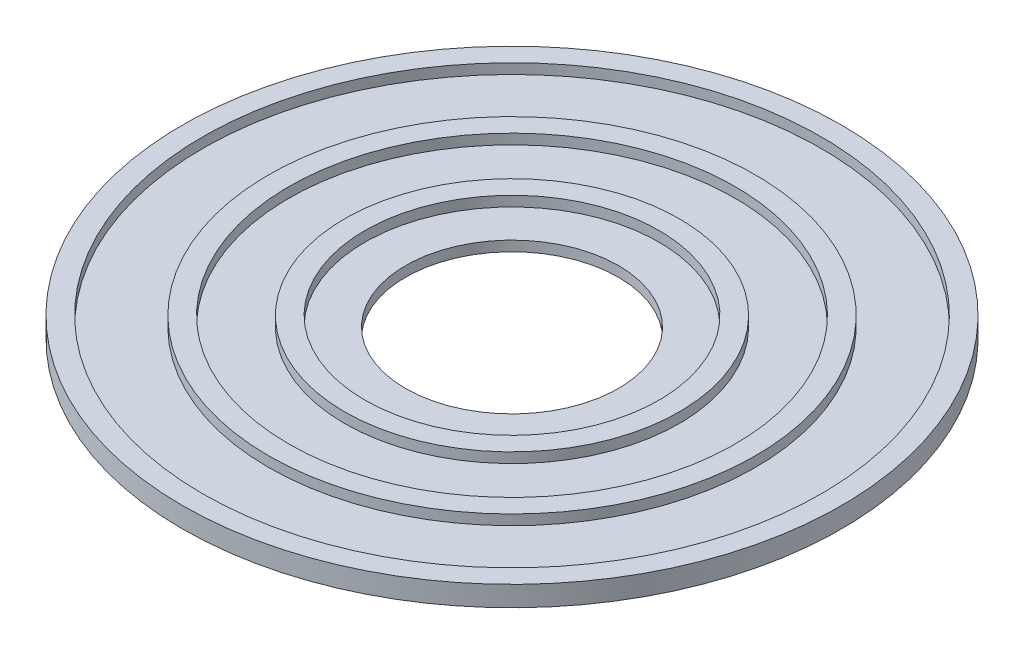
SolidWorks part; units mm, degrees
material "BUTYL"
ref_plane "Płaszczyzna przednia" through (0, 0, 0) normal (0, 0, 1) x (1, 0, 0)
ref_plane "Płaszczyzna górna" through (0, 0, 0) normal (0, 1, 0) x (1, 0, 0)
ref_plane "Płaszczyzna prawa" through (0, 0, 0) normal (1, 0, 0) x (0, 0, -1)
sketch "Szkic1" plane through (0, 0, 0) normal (0, 1, 0) x (1, 0, 0)
  circle A0 centre (0, 0) radius 32.5
  circle A1 centre (0, 0) radius 10.5
  dimension "D1" = 65
  dimension "D2" = 21
extrude "Dodanie-wyciągnięcie1" add sketch "Szkic1" along normal blind 1
sketch "Szkic2" plane through (0, 1, 0) normal (0, 1, 0) x (1, 0, 0)
  circle A0 centre (0, 0) radius 30.5
  circle A1 centre (0, 0) radius 32.5
  circle A2 centre (0, 0) radius 32.5
  circle A3 centre (0, 0) radius 24
  circle A4 centre (0, 0) radius 22
  circle A5 centre (0, 0) radius 16.5
  circle A6 centre (0, 0) radius 14.5
  circle A7 centre (0, 0) radius 10.5 construction
  circle M2 centre (0, 0) radius 32.5
  dimension "D2" = 2
  dimension "D3" = 2
  dimension "D4" = 2
  dimension "D5" = 4
  dimension "D6" = 6.5
  dimension "D1" = 0
extrude "Dodanie-wyciągnięcie2" add sketch "Szkic2" along normal blind 1 contours A0 M2 | A3 A4 | A5 A6
